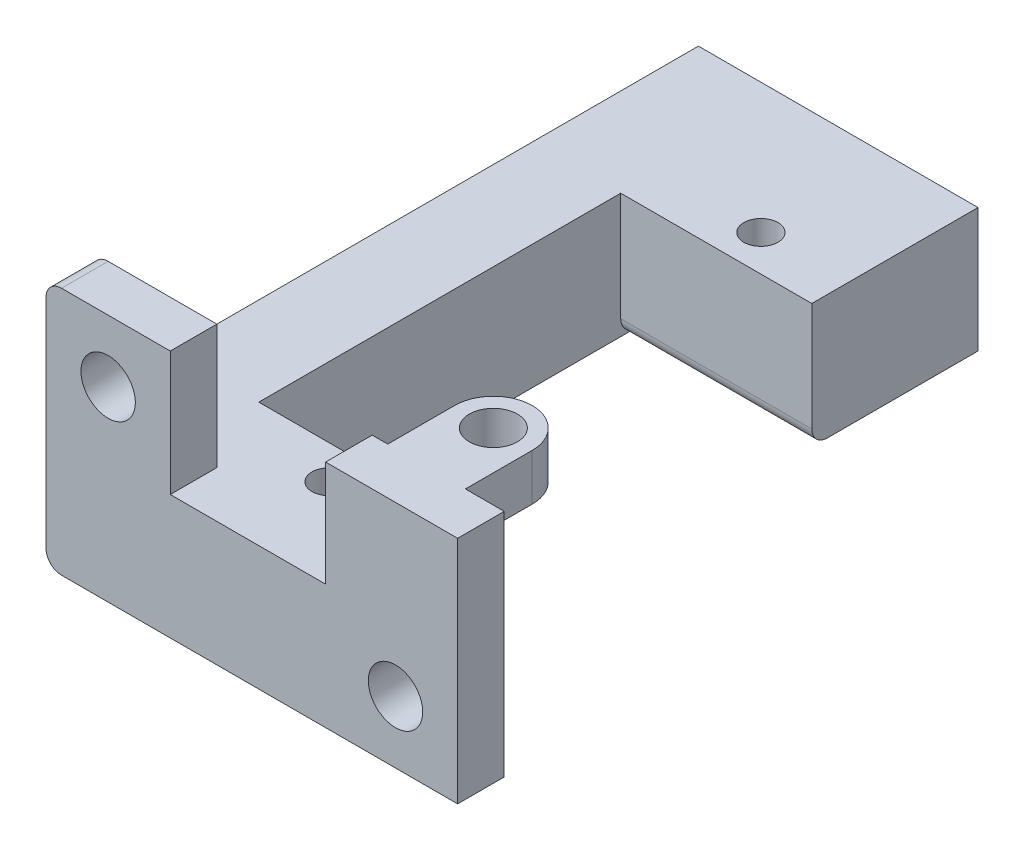
SolidWorks part; units mm, degrees
ref_plane "前视基准面" through (0, 0, 0) normal (0, 0, 1) x (1, 0, 0)
ref_plane "上视基准面" through (0, 0, 0) normal (0, 1, 0) x (1, 0, 0)
ref_plane "右视基准面" through (0, 0, 0) normal (1, 0, 0) x (0, 0, -1)
other "Configuration Table"
sketch "草图1" plane through (0, 0, 0) normal (0, 1, 0) x (1, 0, 0)
  line L1 (-9, -20) -> (9, -20)
  line L2 (-9, -20) -> (-9, 20)
  line L3 (-9, 20) -> (9, 20)
  line L4 (9, -20) -> (9, 20)
  line L5 (-9, -20) -> (9, 20) construction
  line L6 (-9, 20) -> (9, -20) construction
  line L7 (9, -14) -> (-3.3, -14)
  line L8 (9, -14) -> (9, 9.3)
  line L9 (9, 9.3) -> (-3.3, 9.3)
  line L10 (-3.3, -14) -> (-3.3, 9.3)
  point P0 (0, 0)
  dimension "D1" = 40
  dimension "D2" = 18
  dimension "D3" = 23.3
  dimension "D4" = 29.3
  dimension "D5" = 12.3
extrude "凸台-拉伸1" add sketch "草图1" along normal mid plane 8 contours L7 L10 L9 L4 L3 L2 L1
sketch "草图3" plane through (0, 0, 20) normal (0, 0, 1) x (1, 0, 0)
  line L0 (-9, 4) -> (9, 4) construction
  line L3 (-1, 4) -> (20, 4)
  line L4 (20, -4) -> (20, 4)
  line L5 (-9, -4) -> (20, -4)
  line L9 (-9, -4) -> (-9, 12)
  line L10 (-9, 12) -> (-1, 12)
  line L12 (-1, 4) -> (-1, 12)
  point P0 (0, 0)
  dimension "D1" = 29
  dimension "D2" = 8
  dimension "D3" = 16
extrude "凸台-拉伸2" add sketch "草图3" along normal blind 2 and the other way blind 1
ref_plane "基准面1" through (0, 7.81, 0) normal (0, 1, 0) x (1, 0, 0)
sketch "草图4" plane through (0, 7.81, 0) normal (0, 1, 0) x (1, 0, 0)
  line L0 (10, -14.7) -> (10, -22)
  line L1 (20, -22) -> (-1, -22) construction
  line L2 (10, -22) -> (15, -22)
  line L3 (15, -22) -> (15, -14.7)
  line L4 (9, -19) -> (9, -14) construction
  arc A0 (15, -14.7) -> (10, -14.7) centre (12.5, -14.7) ccw
  circle A1 centre (12.5, -14.7) radius 1.55
  dimension "D1" = 6
  dimension "D2" = 5
  dimension "D3" = 7.3
  dimension "D4" = 3.1
extrude "凸台-拉伸3" add sketch "草图4" along normal blind 3 separate body
sketch "草图5" plane through (0, 0, 19) normal (0, 0, -1) x (-1, 0, 0)
  line L0 (-10, 10.81) -> (-15, 10.81) construction
  line L1 (-20, 4) -> (-9, 4)
  line L2 (-20, 4) -> (-20, 10.81)
  line L3 (-20, 10.81) -> (-9, 10.81)
  line L4 (-9, 4) -> (-9, 10.81)
  line L5 (-9, 4) -> (-9, -4) construction
  line L6 (-9, 4) -> (-9, -4) construction
extrude "凸台-拉伸4" add sketch "草图5" against normal up to surface (3 mm away) up to face at (3.3333, 4, 22)
sketch "草图6" plane through (0, 0, 19) normal (0, 0, -1) x (-1, 0, 0)
  line L0 (-13.5, 0) -> (-11.75, 0) construction
  circle A0 centre (-13.5, 0) radius 1.75
  circle A2 centre (5, 8) radius 1.75
  dimension "D2" = 5
  dimension "D3" = 3.5
  dimension "D1" = 13.5
  dimension "D5" = 3.5
  dimension "D4" = 8
extrude "切除-拉伸1" cut sketch "草图6" against normal blind 3
sketch "草图7" plane through (0, 0, 19) normal (0, 0, -1) x (-1, 0, 0)
  line L7 (-20, 10.81) -> (-20, -4)
  line L8 (-20, 10.81) -> (-17.5, 10.81)
  line L9 (-15, 10.81) -> (-20, 10.81) construction
  line L10 (-20, -4) -> (-17.5, -4)
  line L11 (-9, -4) -> (-20, -4) construction
  line L12 (-17.5, -4) -> (-17.5, 10.81)
  line L13 (-15, 7.81) -> (-15, 10.81) construction
  dimension "D1" = 2.5
extrude "切除-拉伸2" cut sketch "草图7" against normal through all
fillet "圆角1" radius 1 2 edges at (-9, -4, 1) (-9, 12, 20.5)
fillet "圆角2" radius 1 2 edges at (2.85, -4, 14) (2.85, -4, -9.3)
sketch "草图8" plane through (0, -4, 0) normal (0, -1, 0) x (1, 0, 0)
  line L0 (-8, 22) -> (17.5, 22) construction
  line L1 (-8, -20) -> (9, -20) construction
  line L2 (17.5, 22) -> (17.5, 19) construction
  line L3 (9, -10.3) -> (9, -20) construction
  circle A0 centre (3.4, -11.6231) radius 1.1
  circle A1 centre (3.4, 16.1769) radius 1.1
  dimension "D1" = 2.2
  dimension "D2" = 2.2
  dimension "D3" = 5.8231
  dimension "D4" = 8.3769
  dimension "D5" = 14.1
  dimension "D6" = 5.6
extrude "切除-拉伸3" cut sketch "草图8" against normal through all
